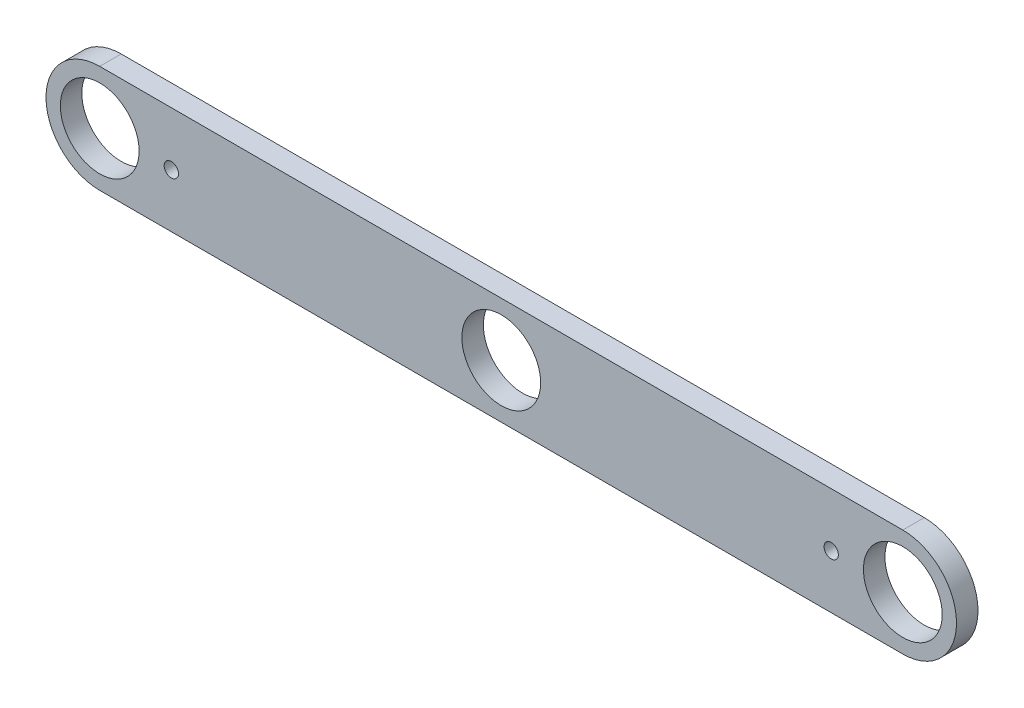
SolidWorks part; units mm, degrees
ref_plane "Front Plane" through (0, 0, 0) normal (0, 0, 1) x (1, 0, 0)
ref_plane "Top Plane" through (0, 0, 0) normal (0, 1, 0) x (1, 0, 0)
ref_plane "Right Plane" through (0, 0, 0) normal (1, 0, 0) x (0, 0, -1)
sketch "Sketch1" plane through (0, 0, 0) normal (0, 0, 1) x (1, 0, 0)
  line L0 (112.155, 0) -> (-112.155, 0) construction
  line L1 (112.155, -15) -> (-112.155, -15)
  line L2 (112.155, 15) -> (-112.155, 15)
  arc A0 (112.155, -15) -> (112.155, 15) centre (112.155, 0) ccw
  arc A1 (-112.155, 15) -> (-112.155, -15) centre (-112.155, 0) ccw
  circle A2 centre (0, 0) radius 11
  circle A3 centre (112.155, 0) radius 11
  circle A4 centre (-112.155, 0) radius 11
  circle A5 centre (-92.155, 0) radius 2
  circle A6 centre (92.155, 0) radius 2
  point P2 (0, 0)
  dimension "D1" = 22
  dimension "D2" = 15
  dimension "D4" = 4
  dimension "D5" = 20
  dimension "D3" = 224.31
  dimension "D6" = 20
extrude "Boss-Extrude1" add sketch "Sketch1" along normal blind 6
